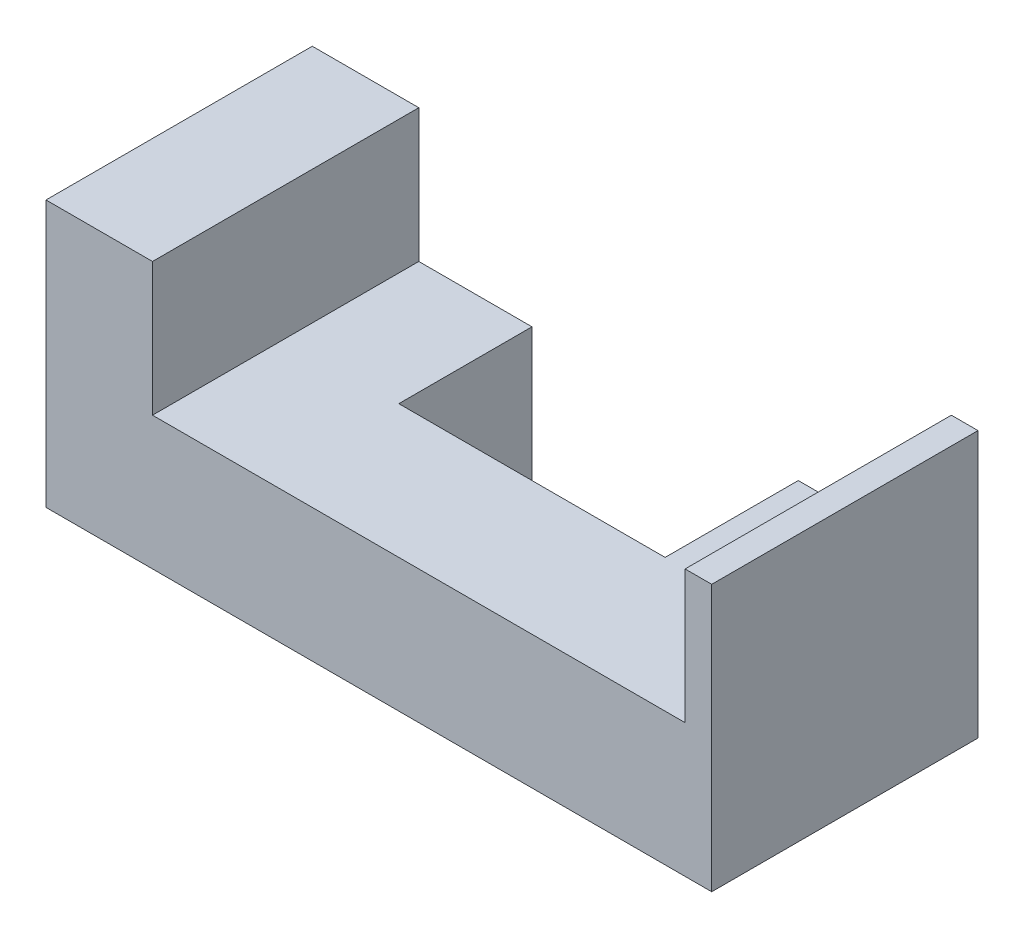
SolidWorks part; units mm, degrees
ref_plane "前基準面" through (0, 0, 0) normal (0, 0, 1) x (1, 0, 0)
ref_plane "上基準面" through (0, 0, 0) normal (0, 1, 0) x (1, 0, 0)
ref_plane "右基準面" through (0, 0, 0) normal (1, 0, 0) x (0, 0, -1)
sketch "草圖1" plane through (0, 0, 0) normal (0, 0, 1) x (1, 0, 0)
  line L1 (-25, 10) -> (25, 10)
  line L2 (-25, 10) -> (-25, -10)
  line L3 (-25, -10) -> (25, -10)
  line L4 (25, 10) -> (25, -10)
  line L5 (-25, 10) -> (25, -10) construction
  line L6 (-25, -10) -> (25, 10) construction
  line L7 (-17, 10) -> (23, 10)
  line L8 (-17, 10) -> (-17, 0)
  line L9 (-17, 0) -> (23, 0)
  line L10 (23, 10) -> (23, 0)
  point P0 (0, 0)
  dimension "D1" = 50
  dimension "D2" = 20
  dimension "D3" = 2
  dimension "D4" = 40
  dimension "D5" = 10
extrude "填料-伸長1" add sketch "草圖1" along normal blind 20 contours L1 L10 L9 L8 L2 L3 L4
sketch "草圖2" plane through (0, 0, 0) normal (0, 1, 0) x (1, 0, 0)
  line L0 (-17, 0) -> (23, 0) construction
  line L1 (11.5, 0) -> (-8.5, 0)
  line L2 (11.5, 0) -> (11.5, -10)
  line L3 (11.5, -10) -> (-8.5, -10)
  line L4 (-8.5, 0) -> (-8.5, -10)
  dimension "D1" = 8.5
  dimension "D2" = 11.5
  dimension "D3" = 10
extrude "除料-伸長1" cut sketch "草圖2" against normal blind 10
